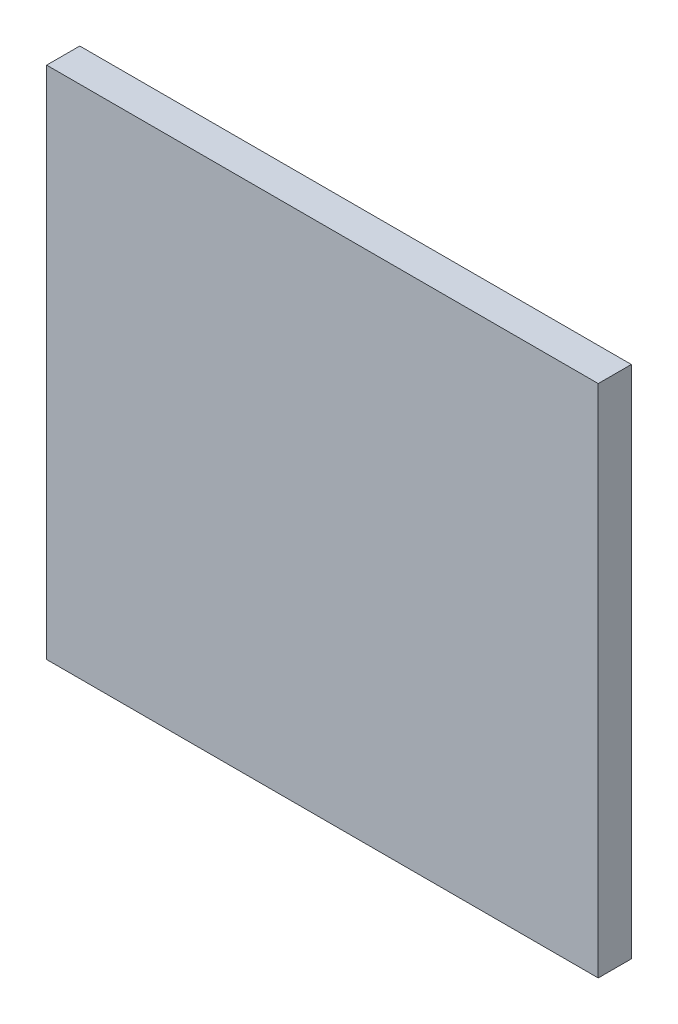
SolidWorks part; units mm, degrees
ref_plane "Front Plane" through (0, 0, 0) normal (0, 0, 1) x (1, 0, 0)
ref_plane "Top Plane" through (0, 0, 0) normal (0, 1, 0) x (1, 0, 0)
ref_plane "Right Plane" through (0, 0, 0) normal (1, 0, 0) x (0, 0, -1)
sketch "Sketch1" plane through (0, 0, 0) normal (0, 0, 1) x (1, 0, 0)
  line L1 (-15, -14) -> (15, -14)
  line L2 (-15, -14) -> (-15, 14)
  line L3 (-15, 14) -> (15, 14)
  line L4 (15, -14) -> (15, 14)
  line L5 (-15, -14) -> (15, 14) construction
  line L6 (-15, 14) -> (15, -14) construction
  point P0 (0, 0)
  dimension "D1" = 30
  dimension "D2" = 28
extrude "Boss-Extrude1" add sketch "Sketch1" along normal blind 1.8
